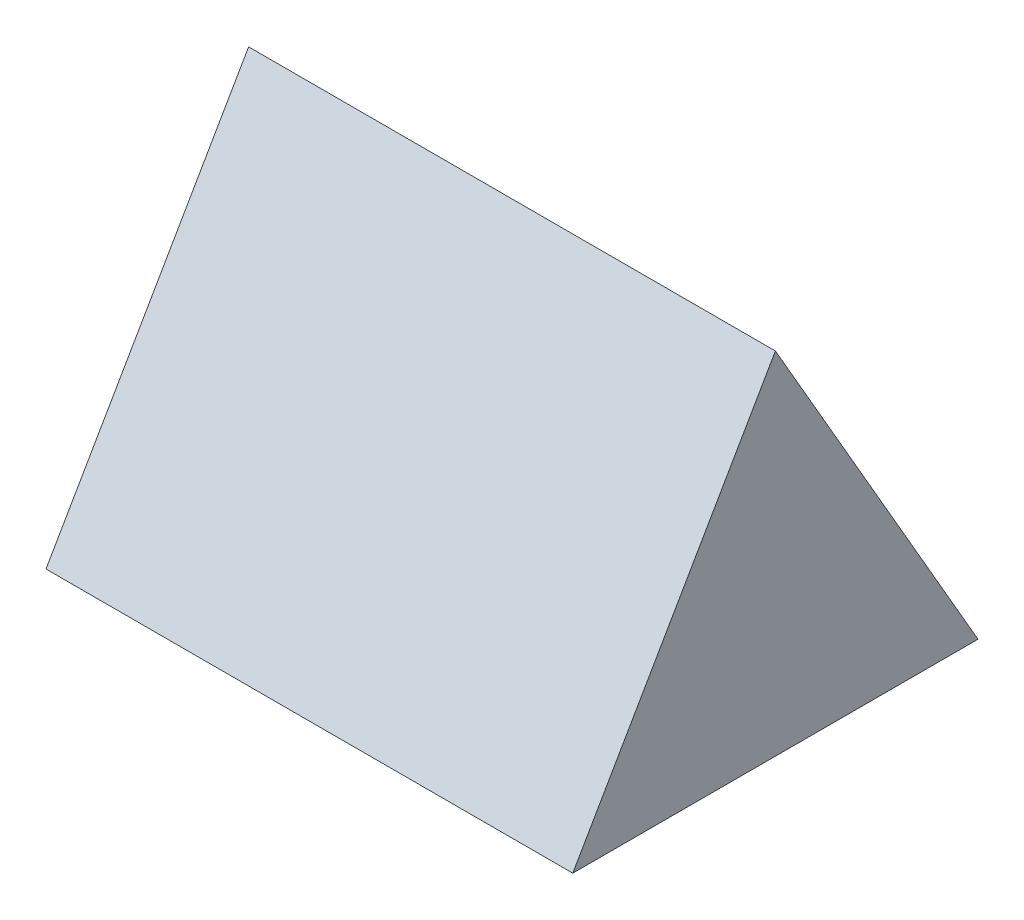
SolidWorks part; units mm, degrees
ref_plane "前视基准面" through (0, 0, 0) normal (0, 0, 1) x (1, 0, 0)
ref_plane "上视基准面" through (0, 0, 0) normal (0, 1, 0) x (1, 0, 0)
ref_plane "右视基准面" through (0, 0, 0) normal (1, 0, 0) x (0, 0, -1)
sketch "草图1" plane through (0, 0, 0) normal (1, 0, 0) x (0, 0, -1)
  line L0 (0, 0) -> (50000, 0) construction
  line L2 (-50, -43.3013) -> (50, -43.3013)
  line L3 (50, -43.3013) -> (0, 43.3013)
  line L4 (0, 43.3013) -> (-50, -43.3013)
  line L5 (0, 43.3013) -> (0, -43.3013) construction
  point P7 (0, 0)
  dimension "D1" = 100
  dimension "D2" = 100
  dimension "D3" = 100
  dimension "D4" = 90
  dimension "D5" = 43.3013
  dimension "D6" = 43.3013
extrude "凸台-拉伸1" add sketch "草图1" along normal mid plane 130
